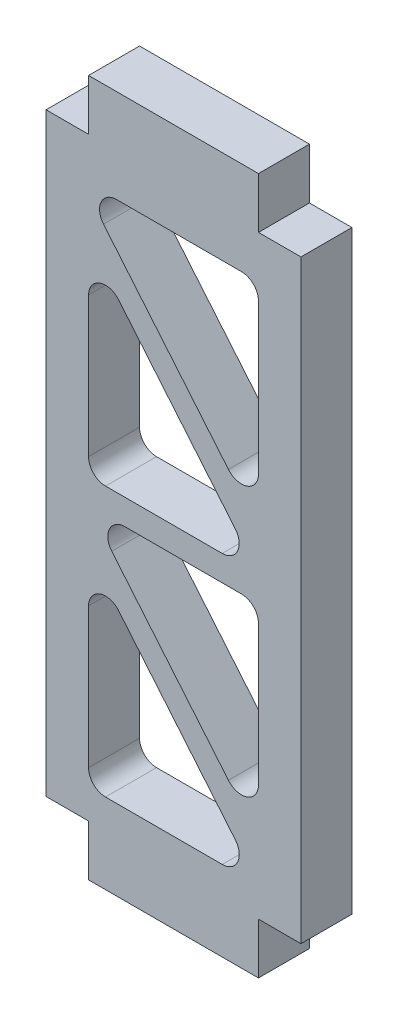
SolidWorks part; units mm, degrees
material "Acrílico (Impacto medio-alto)"
ref_plane "Alzado" through (0, 0, 0) normal (0, 0, 1) x (1, 0, 0)
ref_plane "Planta" through (0, 0, 0) normal (0, 1, 0) x (1, 0, 0)
ref_plane "Vista lateral" through (0, 0, 0) normal (1, 0, 0) x (0, 0, -1)
sketch "Croquis1" plane through (0, 0, 0) normal (0, 0, 1) x (1, 0, 0)
  line L0 (0, 0) -> (0, 14.9643) construction
  line L1 (7.5, -20.5) -> (-7.5, -20.5)
  line L2 (7.5, -20.5) -> (7.5, 20.5)
  line L3 (7.5, 20.5) -> (-7.5, 20.5)
  line L4 (-7.5, -20.5) -> (-7.5, 20.5)
  line L5 (7.5, -20.5) -> (-7.5, 20.5) construction
  line L6 (7.5, 20.5) -> (-7.5, -20.5) construction
  line L7 (0, 0) -> (-16.1003, 0) construction
  line L8 (-5, -23.5) -> (-10, -23.5)
  line L9 (-5, 17.5) -> (-10, 17.5)
  line L10 (-5, 17.5) -> (-5, 23.5)
  line L11 (-5, 23.5) -> (-10, 23.5)
  line L12 (-10, 17.5) -> (-10, 23.5)
  line L13 (-5, 17.5) -> (-10, 23.5) construction
  line L14 (-5, 23.5) -> (-10, 17.5) construction
  line L15 (-10, -17.5) -> (-10, -23.5)
  line L16 (-5, -17.5) -> (-10, -17.5)
  line L17 (-5, -17.5) -> (-5, -23.5)
  line L18 (5, -17.5) -> (5, -23.5)
  line L19 (5, -17.5) -> (10, -17.5)
  line L20 (10, -17.5) -> (10, -23.5)
  line L21 (5, -23.5) -> (10, -23.5)
  line L22 (5, 23.5) -> (10, 23.5)
  line L23 (10, 17.5) -> (10, 23.5)
  line L24 (5, 17.5) -> (10, 17.5)
  line L25 (5, 17.5) -> (5, 23.5)
  line L26 (-4.121, 13.3598) -> (3.2318, 4.5365)
  line L27 (5, 5.1767) -> (5, 14)
  line L28 (4, 15) -> (-3.3528, 15)
  line L29 (-3.2318, 9.9497) -> (3.6332, 1.7117)
  line L30 (2.865, 0.0716) -> (-4, 0.0716)
  line L31 (-5, 1.0716) -> (-5, 9.3095)
  line L32 (-2.865, -1.4284) -> (4, -1.4284)
  line L33 (5, -2.4284) -> (5, -10.6664)
  line L34 (3.2318, -11.3066) -> (-3.6332, -3.0686)
  line L35 (-3.2318, -5.8934) -> (3.638, -14.1372)
  line L36 (2.8698, -15.7773) -> (-4, -15.7773)
  line L37 (-5, -14.7773) -> (-5, -6.5336)
  arc A0 (-4.121, 13.3598) -> (-3.3528, 15) centre (-3.3528, 14) cw
  arc A1 (3.2318, 4.5365) -> (5, 5.1767) centre (4, 5.1767) ccw
  arc A2 (5, 14) -> (4, 15) centre (4, 14) ccw
  arc A3 (-3.2318, 9.9497) -> (-5, 9.3095) centre (-4, 9.3095) ccw
  arc A4 (-4, 0.0716) -> (-5, 1.0716) centre (-4, 1.0716) cw
  arc A5 (3.6332, 1.7117) -> (2.865, 0.0716) centre (2.865, 1.0716) cw
  arc A6 (4, -1.4284) -> (5, -2.4284) centre (4, -2.4284) cw
  arc A7 (5, -10.6664) -> (3.2318, -11.3066) centre (4, -10.6664) cw
  arc A8 (-2.865, -1.4284) -> (-3.6332, -3.0686) centre (-2.865, -2.4284) ccw
  arc A9 (-3.2318, -5.8934) -> (-5, -6.5336) centre (-4, -6.5336) ccw
  arc A10 (3.638, -14.1372) -> (2.8698, -15.7773) centre (2.8698, -14.7773) cw
  arc A11 (-4, -15.7773) -> (-5, -14.7773) centre (-4, -14.7773) cw
  point P0 (0, 0)
  point P43 (-5.4878, 15)
  point P46 (5, 2.4146)
  point P49 (5, 14.4146)
  point P52 (-5, 12.0716)
  point P55 (-5, 0.0716)
  point P58 (5, 0.0716)
  point P61 (5, -1.4284)
  point P64 (5, -13.4284)
  point P67 (-5, -1.4284)
  point P70 (-5, -3.7715)
  point P75 (-5.1411, -15.7707)
  dimension "D12" = 1
  dimension "D15" = 2.5
  dimension "D1" = 6
  dimension "D2" = 15
  dimension "D3" = 41
  dimension "D4" = 5
  dimension "D5" = 12
  dimension "D6" = 12
  dimension "D7" = 12
  dimension "D8" = 12
  dimension "D9" = 1.5
  dimension "D10" = 1.5
  dimension "D11" = 1.5
  dimension "D13" = 5.5
  dimension "D14" = 2.5
extrude "Saliente-Extruir1" add sketch "Croquis1" along normal blind 3 contours L24 L25 L3 L10 L9 L4 L16 L17 L1 L18 L19 L2
